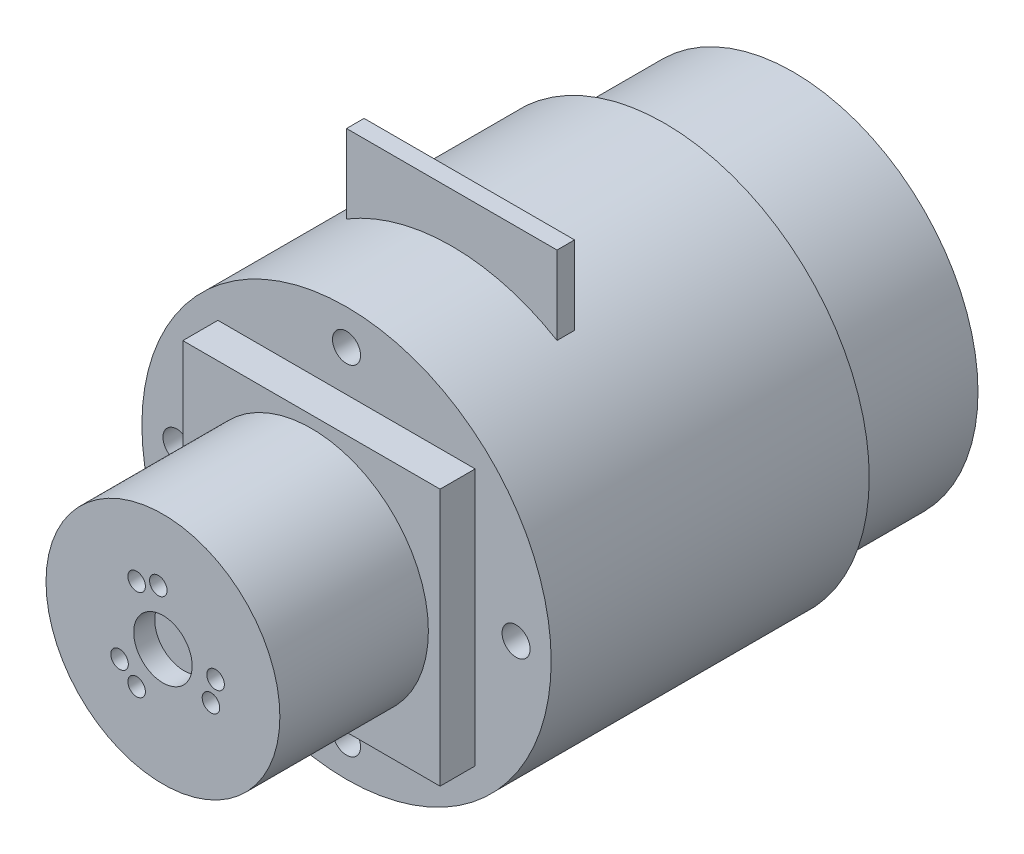
SolidWorks part; units mm, degrees
ref_plane "前视基准面" through (0, 0, 0) normal (0, 0, 1) x (1, 0, 0)
ref_plane "上视基准面" through (0, 0, 0) normal (0, 1, 0) x (1, 0, 0)
ref_plane "右视基准面" through (0, 0, 0) normal (1, 0, 0) x (0, 0, -1)
sketch "草图1" plane through (0, 0, 0) normal (0, 0, 1) x (1, 0, 0)
  circle A0 centre (0, 0) radius 17.5
  dimension "D1" = 35
extrude "凸台-拉伸1" add sketch "草图1" along normal blind 27.2
sketch "草图2" plane through (0, 0, 0) normal (0, 0, -1) x (-1, 0, 0)
  circle A0 centre (0, 0) radius 15.8
  dimension "D1" = 31.6
extrude "凸台-拉伸2" add sketch "草图2" along normal blind 11
sketch "草图3" plane through (0, 0, 27.2) normal (0, 0, 1) x (1, 0, 0)
  line L1 (11, 11) -> (-11, 11)
  line L2 (11, 11) -> (11, -11)
  line L3 (11, -11) -> (-11, -11)
  line L4 (-11, 11) -> (-11, -11)
  line L5 (11, 11) -> (-11, -11) construction
  line L6 (11, -11) -> (-11, 11) construction
  point P0 (0, 0)
  dimension "D1" = 22
  dimension "D2" = 22
extrude "凸台-拉伸3" add sketch "草图3" along normal blind 3
sketch "草图4" plane through (0, 0, 30.2) normal (0, 0, 1) x (1, 0, 0)
  circle A0 centre (0, 0) radius 10
  dimension "D1" = 20
extrude "凸台-拉伸4" add sketch "草图4" along normal blind 12.7
sketch "草图5" plane through (0, 0, 27.2) normal (0, 0, 1) x (1, 0, 0)
  line L0 (0, -19.1827) -> (0, 0) construction
  line L1 (0, -14.5) -> (0, 0) construction
  line L2 (0, 0) -> (17.5, 0) construction
  circle A0 centre (0, -14.5) radius 1.2
  circle A1 centre (0, 0) radius 17.5 construction
  circle A2 centre (-14.5, 0) radius 1.2
  circle A3 centre (0, 14.5) radius 1.2
  circle A4 centre (14.5, 0) radius 1.2
  point P14 (0, 0.9041)
  point P18 (0, 0)
  dimension "D1" = 2.4
  dimension "D3" = 4
  dimension "D2" = 14.5
extrude "切除-拉伸1" cut sketch "草图5" against normal blind 10
ref_plane "基准面1" through (0, 0, 18.2) normal (0, 0, 1) x (1, 0, 0)
sketch "草图6" plane through (0, 0, 18.2) normal (0, 0, 1) x (1, 0, 0)
  line L0 (0, 0) -> (0, 14.5) construction
  line L1 (0, 14.5) -> (0, 20.7692) construction
  line L2 (-9, 15.0083) -> (-9, 21.7083)
  line L3 (-9, 21.7083) -> (9, 21.7083)
  line L4 (9, 15.0083) -> (9, 21.7083)
  arc A0 (9, 15.0083) -> (-9, 15.0083) centre (0, 0) ccw
  point P11 (0, 21.7083)
  dimension "D1" = 35
  dimension "D2" = 9
  dimension "D3" = 6.7
extrude "凸台-拉伸5" add sketch "草图6" against normal blind 1.5
sketch "草图8" plane through (0, 0, 42.9) normal (0, 0, 1) x (1, 0, 0)
  circle A0 centre (0, 0) radius 2.5
  dimension "D1" = 5
extrude "切除-拉伸2" cut sketch "草图8" against normal blind 1.8
sketch "草图9" plane through (0, 0, 42.9) normal (0, 0, 1) x (1, 0, 0)
  line L0 (0, 0) -> (10, 0) construction
  line L1 (0, 0) -> (9.0631, -4.2262) construction
  circle A0 centre (0, 0) radius 10 construction
  circle A1 centre (4.5, 0) radius 0.75
  circle A2 centre (4.1064, -1.9149) radius 0.75
  circle A3 centre (-2.25, -3.8971) radius 0.75
  circle A4 centre (-3.7115, -2.5989) radius 0.75
  circle A5 centre (-2.25, 3.8971) radius 0.75
  circle A6 centre (-0.3949, 4.5137) radius 0.75
  point P21 (0, 0)
  dimension "D1" = 1.5
  dimension "D4" = 1.5
  dimension "D2" = 4.5
  dimension "D3" = 25
  dimension "D5" = 3
extrude "切除-拉伸3" cut sketch "草图9" against normal blind 2
